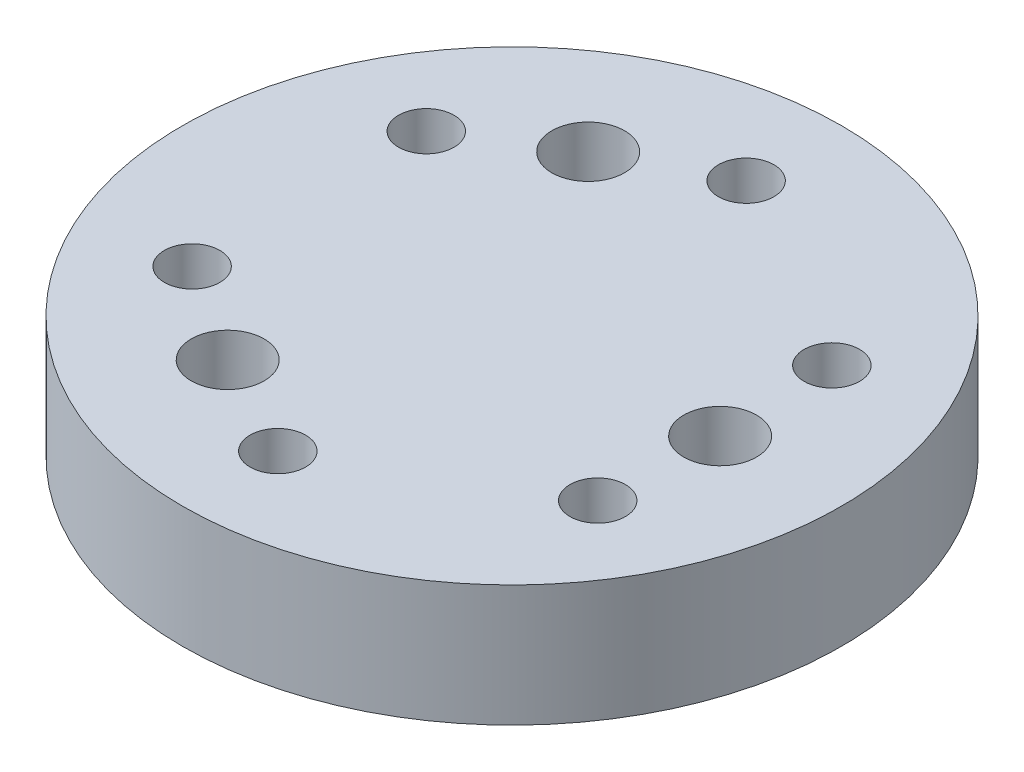
SolidWorks part; units mm, degrees
ref_plane "前视基准面" through (0, 0, 0) normal (0, 0, 1) x (1, 0, 0)
ref_plane "上视基准面" through (0, 0, 0) normal (0, 1, 0) x (1, 0, 0)
ref_plane "右视基准面" through (0, 0, 0) normal (1, 0, 0) x (0, 0, -1)
other "Configuration Table"
sketch "草图1" plane through (0, 0, 0) normal (0, 1, 0) x (1, 0, 0)
  circle A0 centre (0, 0) radius 17.6
  circle A1 centre (0, 0) radius 19
  dimension "D1" = 35.2
  dimension "D2" = 38
extrude "凸台-拉伸1" add sketch "草图1" along normal blind 3
sketch "草图2" plane through (0, 3, 0) normal (0, 1, 0) x (1, 0, 0)
  circle A0 centre (0, 0) radius 19
extrude "凸台-拉伸2" add sketch "草图2" along normal blind 4
sketch "草图3" plane through (0, 7, 0) normal (0, 1, 0) x (1, 0, 0)
  circle A0 centre (0, 0) radius 13.5 construction
  circle A1 centre (0, 0) radius 12 construction
  circle A2 centre (0, 13.5) radius 1.6
  circle A3 centre (11.6913, 6.75) radius 1.6
  circle A4 centre (11.6913, -6.75) radius 1.6
  circle A5 centre (0, -13.5) radius 1.6
  circle A6 centre (-11.6913, -6.75) radius 1.6
  circle A7 centre (-11.6913, 6.75) radius 1.6
  circle A9 centre (12, 0) radius 2.1
  circle A10 centre (-6, -10.3923) radius 2.1
  circle A11 centre (-6, 10.3923) radius 2.1
  dimension "D1" = 27
  dimension "D2" = 24
  dimension "D3" = 3.2
  dimension "D5" = 4.2
  dimension "D4" = 6
  dimension "D6" = 3
extrude "切除-拉伸1" cut sketch "草图3" against normal through all
